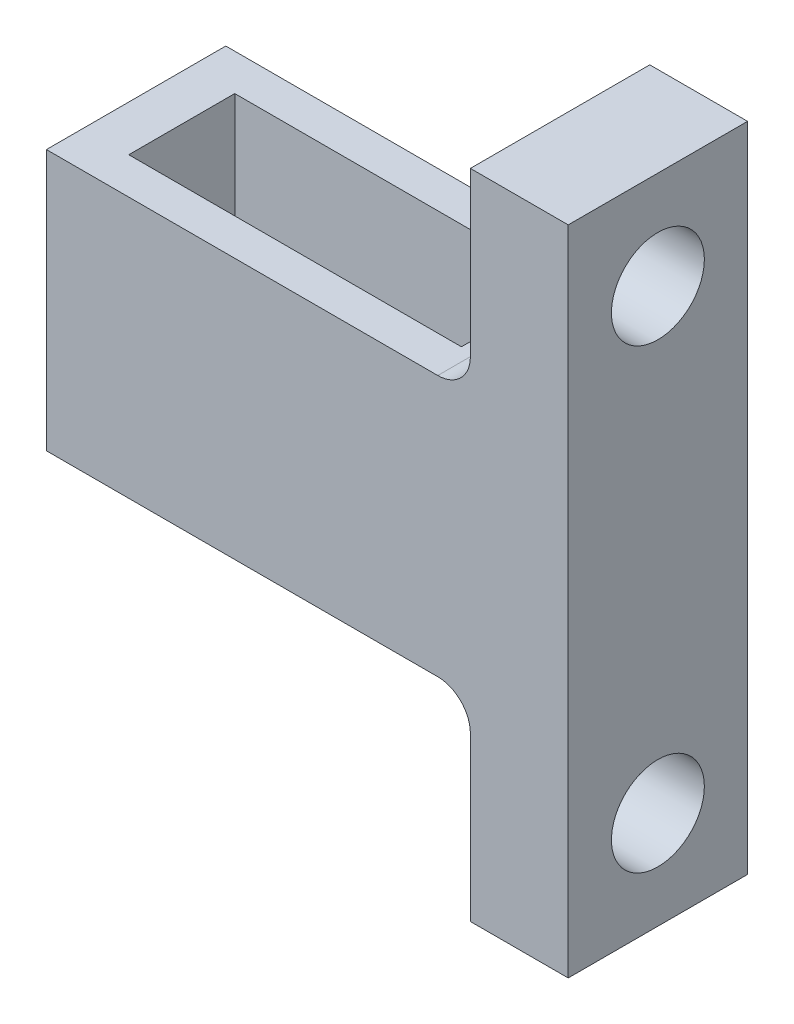
SolidWorks part; units mm, degrees
ref_plane "Front Plane" through (0, 0, 0) normal (0, 0, 1) x (1, 0, 0)
ref_plane "Top Plane" through (0, 0, 0) normal (0, 1, 0) x (1, 0, 0)
ref_plane "Right Plane" through (0, 0, 0) normal (1, 0, 0) x (0, 0, -1)
sketch "Sketch2" plane through (0, 0, 0) normal (0, 1, 0) x (1, 0, 0)
  line L0 (-13, 5.5) -> (13, -5.5) construction
  line L1 (-13, -5.5) -> (13, -5.5)
  line L2 (-13, -5.5) -> (-13, 5.5)
  line L3 (-13, 5.5) -> (13, 5.5)
  line L4 (13, -5.5) -> (13, 5.5)
  line L5 (-13, -5.5) -> (13, 5.5) construction
  line L6 (-10.2, 3.25) -> (10.2, -3.25) construction
  line L7 (-10.2, -3.25) -> (10.2, -3.25)
  line L8 (-10.2, -3.25) -> (-10.2, 3.25)
  line L9 (-10.2, 3.25) -> (10.2, 3.25)
  line L10 (10.2, -3.25) -> (10.2, 3.25)
  line L11 (10.2, 3.25) -> (-10.2, -3.25) construction
  point P1 (0, 0)
  point P6 (0, 0)
  point P11 (10.2, 0)
  dimension "D1" = 26
  dimension "D2" = 11
  dimension "D3" = 20.4
  dimension "D4" = 6.5
  dimension "D5" = 0
  dimension "D6" = 10.2
extrude "Boss-Extrude1" add sketch "Sketch2" along normal blind 10
sketch "Sketch3" plane through (0, 0, 0) normal (0, -1, 0) x (1, 0, 0)
  line L0 (-10.2, 3.25) -> (10.2, 3.25) construction
  line L1 (-13, 5.5) -> (13, 5.5)
  line L2 (-13, 5.5) -> (-13, -5.5)
  line L3 (-13, -5.5) -> (13, -5.5)
  line L4 (13, 5.5) -> (13, -5.5)
  line L5 (10.2, -3.25) -> (-10.2, -3.25) construction
  line L6 (-8.7, 3.25) -> (-6.2, 3.25)
  line L7 (-8.7, 3.25) -> (-8.7, -3.25)
  line L8 (-8.7, -3.25) -> (-6.2, -3.25)
  line L9 (-6.2, 3.25) -> (-6.2, -3.25)
  line L10 (-10.2, -3.25) -> (-10.2, 3.25) construction
  line L11 (-1.5, 3.25) -> (1, 3.25)
  line L12 (-1.5, 3.25) -> (-1.5, -3.25)
  line L13 (-1.5, -3.25) -> (1, -3.25)
  line L14 (1, 3.25) -> (1, -3.25)
  line L15 (6.2, 3.25) -> (8.7, 3.25)
  line L16 (6.2, 3.25) -> (6.2, -3.25)
  line L17 (6.2, -3.25) -> (8.7, -3.25)
  line L18 (8.7, 3.25) -> (8.7, -3.25)
  line L19 (10.2, 3.25) -> (10.2, -3.25) construction
  point P26 (-7.45, 3.25)
  point P27 (-0.25, 3.25)
  dimension "D1" = 2.5
  dimension "D2" = 2.5
  dimension "D3" = 2.5
  dimension "D4" = 1.5
  dimension "D5" = 1.5
  dimension "D6" = 7.2
extrude "Boss-Extrude2" add sketch "Sketch3" along normal blind 6
sketch "Sketch4" plane through (13, 0, 0) normal (1, 0, 0) x (0, 0, -1)
  line L0 (5.5, 10) -> (5.5, -6) construction
  line L1 (-5.5, 22) -> (5.5, 22)
  line L2 (-5.5, 22) -> (-5.5, -18)
  line L3 (-5.5, -18) -> (5.5, -18)
  line L4 (5.5, 22) -> (5.5, -18)
  line L5 (-5.5, 10) -> (5.5, 10) construction
  circle A0 centre (0, 16) radius 2.85
  circle A1 centre (0, -11.9958) radius 2.85
  dimension "D3" = 5.7
  dimension "D5" = 5.7
  dimension "D1" = 40
  dimension "D2" = 12
  dimension "D4" = 6
  dimension "D6" = 6.0042
  dimension "D7" = 5.5
  dimension "D8" = 5.5
extrude "Boss-Extrude3" add sketch "Sketch4" along normal blind 6
fillet "Fillet1" radius 2 2 edges at (13, -6, 0) (13, 10, 0)
